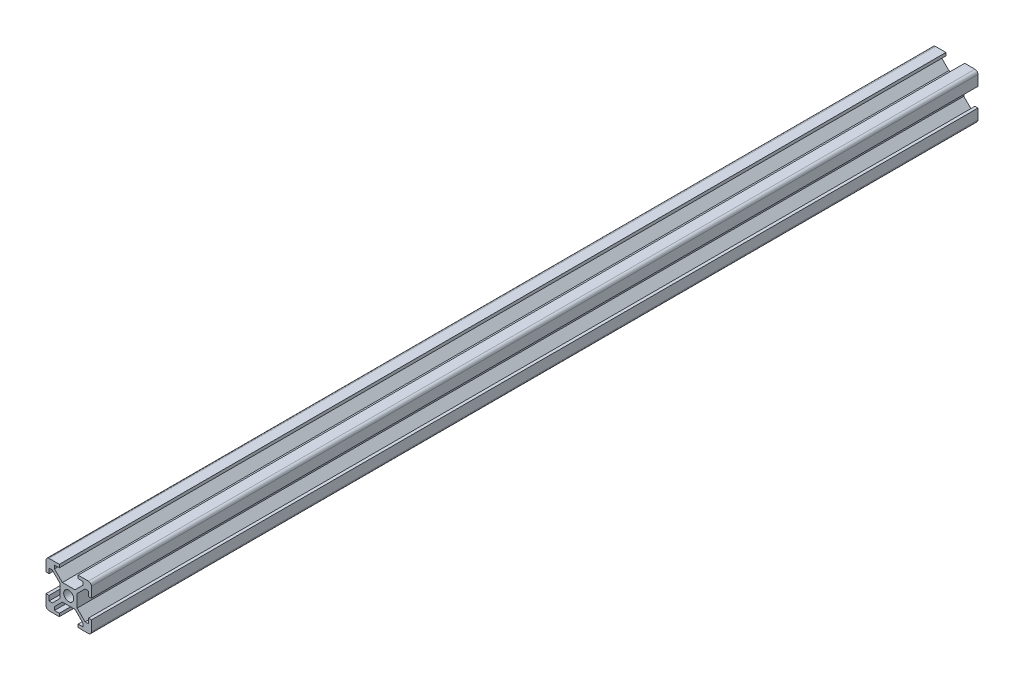
SolidWorks part; units mm, degrees
ref_plane "前视基准面" through (0, 0, 0) normal (0, 0, 1) x (1, 0, 0)
ref_plane "上视基准面" through (0, 0, 0) normal (0, 1, 0) x (1, 0, 0)
ref_plane "右视基准面" through (0, 0, 0) normal (1, 0, 0) x (0, 0, -1)
sketch "草图2" plane through (0, 0, 0) normal (0, 0, 1) x (1, 0, 0)
  line L1 (-2.0929, -2.8) -> (-4.7, -5.4071)
  line L2 (2.8, -2.0929) -> (2.8, 2.0929)
  line L3 (2.8, 2.0929) -> (5.4071, 4.7)
  line L4 (5.4071, 4.7) -> (6.5, 4.7)
  line L5 (6.5, 4.7) -> (6.5, 3.1)
  line L6 (6.5, 3.1) -> (7.5, 3.1)
  line L7 (7.5, 3.1) -> (7.5, 6.5)
  line L8 (-2.8, -2.0929) -> (-5.4071, -4.7)
  line L9 (-2.0929, 2.8) -> (2.0929, 2.8)
  line L10 (3.1, 7.5) -> (6.5, 7.5)
  line L11 (3.1, 6.5) -> (3.1, 7.5)
  line L12 (4.7, 6.5) -> (3.1, 6.5)
  line L13 (4.7, 5.4071) -> (4.7, 6.5)
  line L14 (2.0929, 2.8) -> (4.7, 5.4071)
  line L15 (-5.4071, 4.7) -> (-6.5, 4.7)
  line L16 (-6.5, 4.7) -> (-6.5, 3.1)
  line L17 (-6.5, 3.1) -> (-7.5, 3.1)
  line L18 (-7.5, 3.1) -> (-7.5, 6.5)
  line L19 (-4.7, 6.5) -> (-3.1, 6.5)
  line L20 (-3.1, 6.5) -> (-3.1, 7.5)
  line L21 (-3.1, 7.5) -> (-6.5, 7.5)
  line L22 (-4.7, 5.4071) -> (-4.7, 6.5)
  line L23 (-2.8, 2.0929) -> (-5.4071, 4.7)
  line L24 (-2.8, -2.0929) -> (-2.8, 2.0929)
  line L25 (-2.0929, 2.8) -> (-4.7, 5.4071)
  line L26 (-4.7, -5.4071) -> (-4.7, -6.5)
  line L27 (-3.1, -7.5) -> (-6.5, -7.5)
  line L28 (-3.1, -6.5) -> (-3.1, -7.5)
  line L29 (-4.7, -6.5) -> (-3.1, -6.5)
  line L30 (-7.5, -3.1) -> (-7.5, -6.5)
  line L31 (-6.5, -3.1) -> (-7.5, -3.1)
  line L32 (-6.5, -4.7) -> (-6.5, -3.1)
  line L33 (-5.4071, -4.7) -> (-6.5, -4.7)
  line L34 (2.0929, -2.8) -> (4.7, -5.4071)
  line L35 (4.7, -5.4071) -> (4.7, -6.5)
  line L36 (4.7, -6.5) -> (3.1, -6.5)
  line L37 (3.1, -6.5) -> (3.1, -7.5)
  line L38 (3.1, -7.5) -> (6.5, -7.5)
  line L39 (-2.0929, -2.8) -> (2.0929, -2.8)
  line L40 (7.5, -3.1) -> (7.5, -6.5)
  line L41 (6.5, -3.1) -> (7.5, -3.1)
  line L42 (6.5, -4.7) -> (6.5, -3.1)
  line L43 (5.4071, -4.7) -> (6.5, -4.7)
  line L44 (2.8, -2.0929) -> (5.4071, -4.7)
  arc A0 (7.5, 6.5) -> (6.5, 7.5) centre (6.5, 6.5) ccw
  arc A1 (-7.5, 6.5) -> (-6.5, 7.5) centre (-6.5, 6.5) cw
  arc A2 (-7.5, -6.5) -> (-6.5, -7.5) centre (-6.5, -6.5) ccw
  arc A3 (7.5, -6.5) -> (6.5, -7.5) centre (6.5, -6.5) cw
  circle A4 centre (0, 0) radius 1.65
  point P3 (0, -2.8)
  point P21 (7.5, 7.5)
  point P36 (0, 2.8)
  point P43 (-2.8, 0)
  point P60 (2.8, 0)
  point P61 (7.5, -7.5)
  dimension "D9" = 1
  dimension "D1" = 3.3
  dimension "D5" = 1
  dimension "D8" = 1
extrude "凸台-拉伸1" add sketch "草图2" along normal mid plane 293
